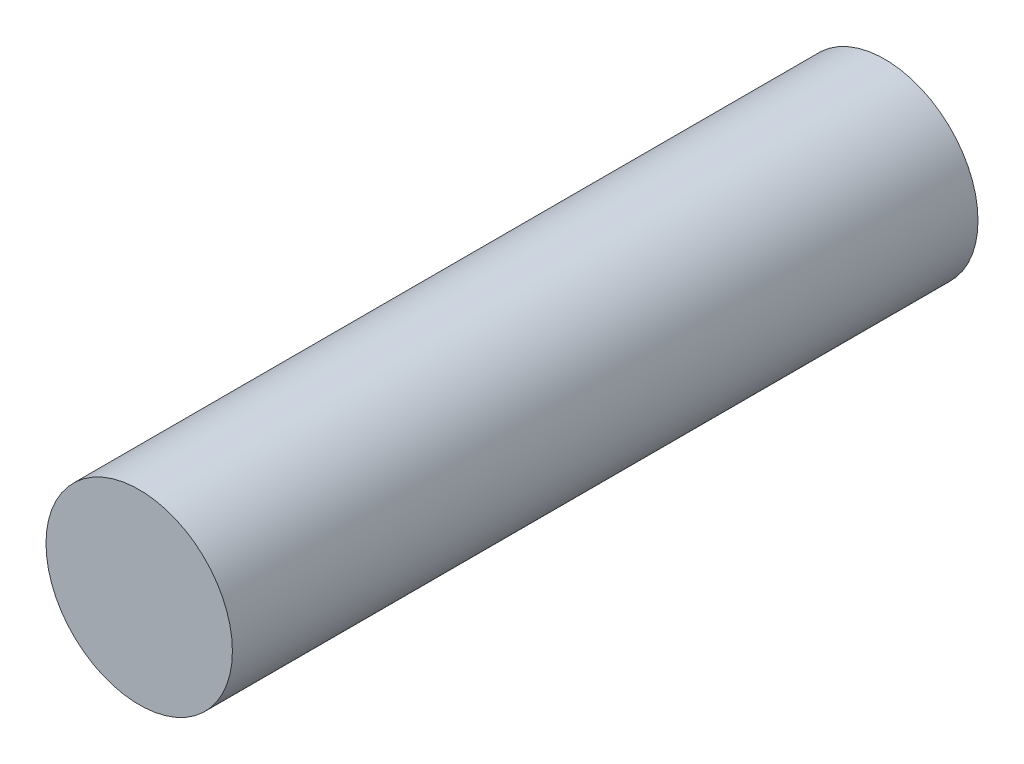
SolidWorks part; units mm, degrees
ref_plane "Front Plane" through (0, 0, 0) normal (0, 0, 1) x (1, 0, 0)
ref_plane "Top Plane" through (0, 0, 0) normal (0, 1, 0) x (1, 0, 0)
ref_plane "Right Plane" through (0, 0, 0) normal (1, 0, 0) x (0, 0, -1)
sketch "Sketch1" plane through (0, 0, 0) normal (0, 0, 1) x (1, 0, 0)
  circle A0 centre (0, 0) radius 38.1
  dimension "D1" = 76.2
extrude "Boss-Extrude1" add sketch "Sketch1" along normal blind 304.8
